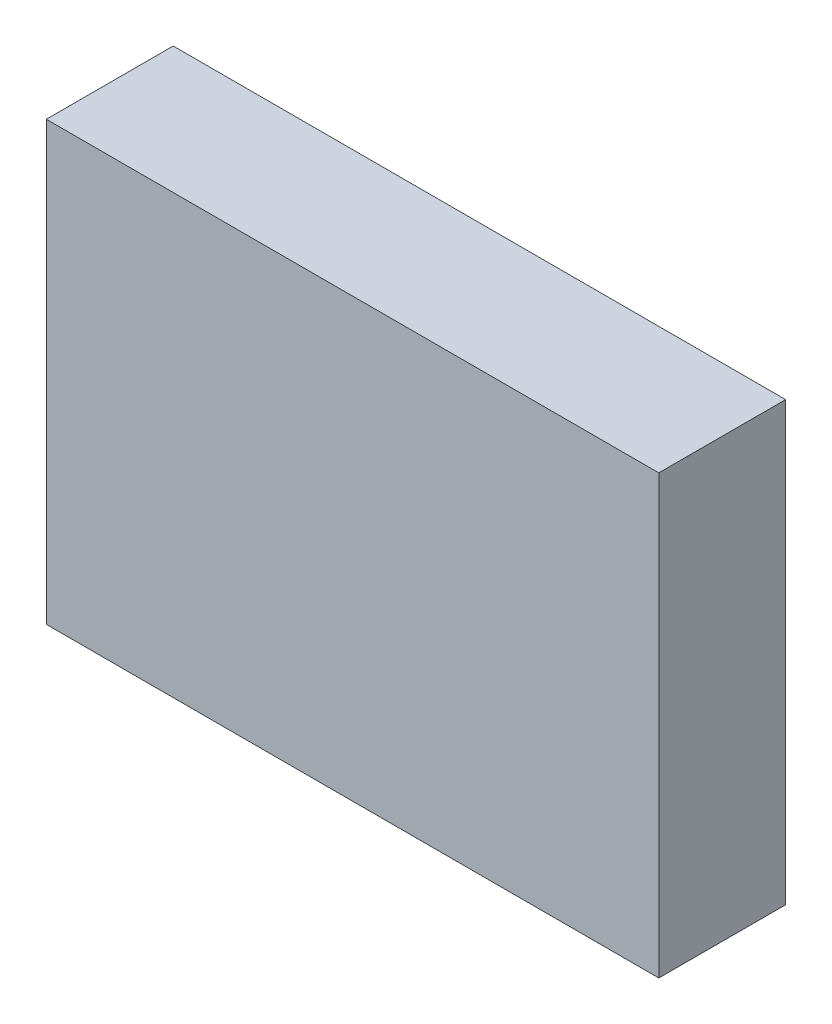
SolidWorks part; units mm, degrees
ref_plane "Front Plane" through (0, 0, 0) normal (0, 0, 1) x (1, 0, 0)
ref_plane "Top Plane" through (0, 0, 0) normal (0, 1, 0) x (1, 0, 0)
ref_plane "Right Plane" through (0, 0, 0) normal (1, 0, 0) x (0, 0, -1)
sketch "Sketch1" plane through (0, 0, 0) normal (0, 0, 1) x (1, 0, 0)
  line L1 (-5.5211, 2.1142) -> (8.4789, 2.1142)
  line L2 (-5.5211, 2.1142) -> (-5.5211, -7.8858)
  line L3 (-5.5211, -7.8858) -> (8.4789, -7.8858)
  line L4 (8.4789, 2.1142) -> (8.4789, -7.8858)
  dimension "D1" = 14
  dimension "D2" = 10
extrude "Boss-Extrude1" add sketch "Sketch1" along normal blind 2.9
